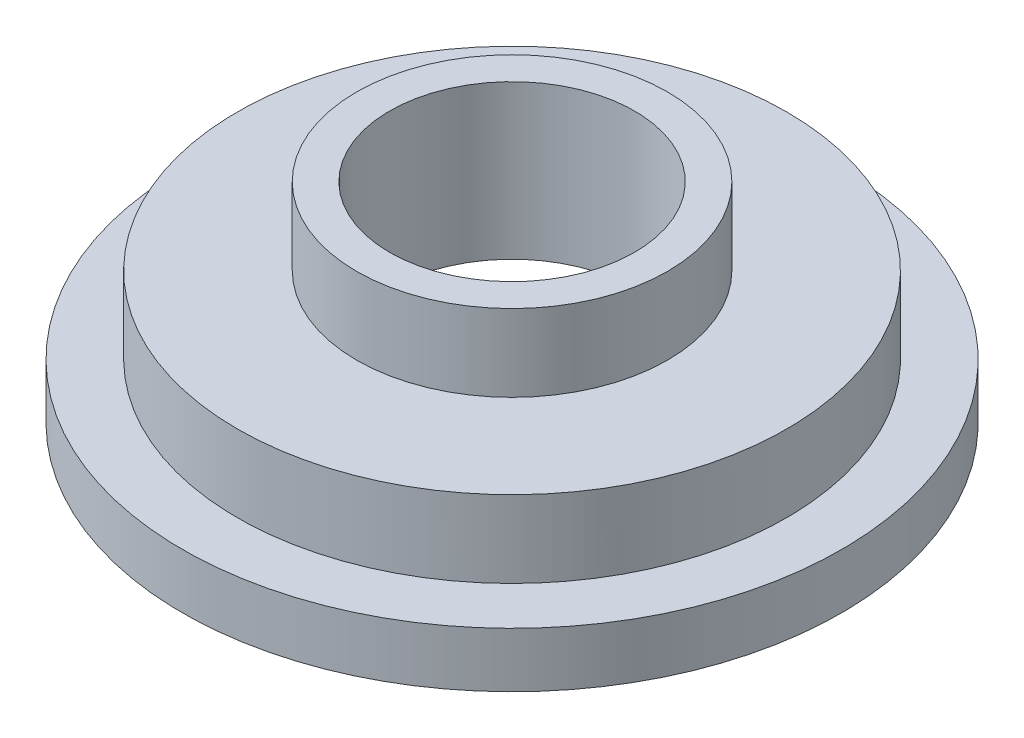
SolidWorks part; units mm, degrees
ref_plane "Front Plane" through (0, 0, 0) normal (0, 0, 1) x (1, 0, 0)
ref_plane "Top Plane" through (0, 0, 0) normal (0, 1, 0) x (1, 0, 0)
ref_plane "Right Plane" through (0, 0, 0) normal (1, 0, 0) x (0, 0, -1)
sketch "Sketch1" plane through (0, 0, 0) normal (0, 1, 0) x (1, 0, 0)
  circle A0 centre (0, 0) radius 11.15
  circle A1 centre (0, 0) radius 25
extrude "Boss-Extrude1" add sketch "Sketch1" along normal blind 7
sketch "Sketch2" plane through (0, 7, 0) normal (0, 1, 0) x (1, 0, 0)
  circle A0 centre (0, 0) radius 11.15
  circle A1 centre (0, 0) radius 14.15
extrude "Boss-Extrude2" add sketch "Sketch2" along normal blind 7
sketch "Sketch3" plane through (0, 0, 0) normal (0, -1, 0) x (1, 0, 0)
  circle A0 centre (0, 0) radius 20
  circle A1 centre (0, 0) radius 30
extrude "Boss-Extrude3" add sketch "Sketch3" along normal blind 5
